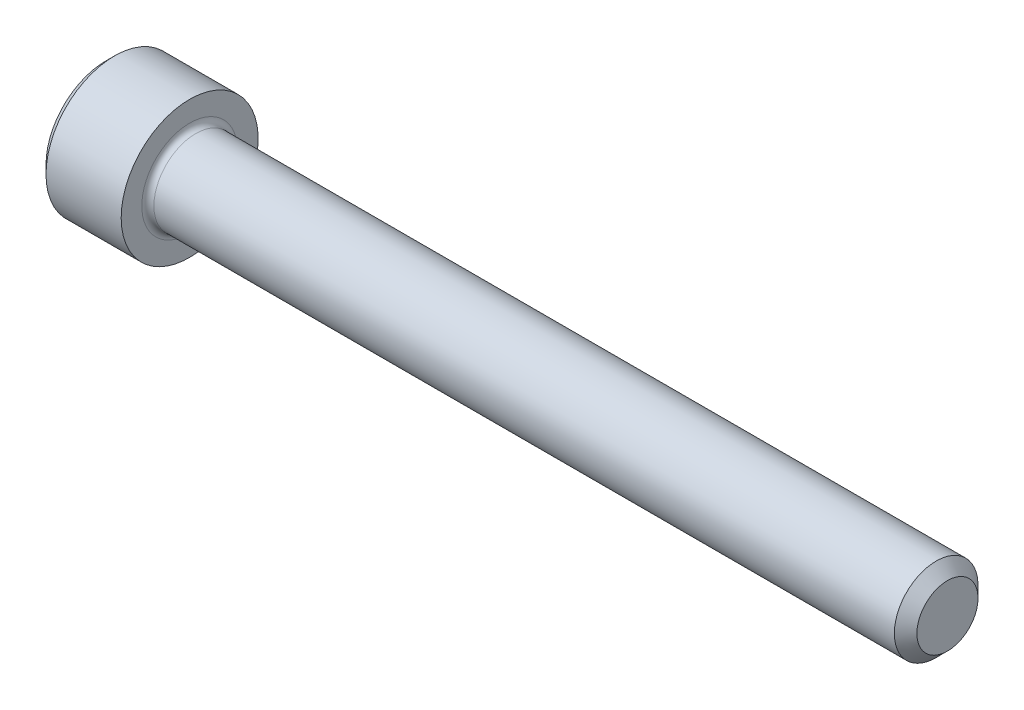
SolidWorks part; units mm, degrees
revolve "Base-Revolve" add sketch "BodySke" angle 360 about L6
sketch "BodySke" plane through (0, 0, 0) normal (0, 0, 1) x (1, 0, 0)
  line L0 (0, 0) -> (0, 2.5146)
  line L1 (0.3556, 2.8702) -> (3.5052, 2.8702)
  line L2 (3.5052, 2.8702) -> (3.5052, 1.7526)
  line L3 (3.5052, 1.7526) -> (34.7828, 1.7526)
  line L4 (35.2552, 1.2802) -> (35.2552, 0)
  line L5 (35.2552, 0) -> (0, 0)
  line L6 (-31.75, 0) -> (127, 0) construction
  line L7 (0, 2.5146) -> (0.3556, 2.8702)
  line L8 (35.2552, 1.2802) -> (34.7828, 1.7526)
  line L9 (0, -2.5146) -> (0.3556, -2.8702) construction
  line L10 (35.2552, -1.2802) -> (34.7828, -1.7526) construction
  line L11 (4.2977, 9.525) -> (4.2977, 3.175) construction
  line L12 (16.2052, 9.525) -> (16.2052, 3.175) construction
  line L13 (-2.8448, 9.525) -> (-2.8448, 3.175) construction
  dimension "Diameter" = 3.5052
  dimension "Head_ht" = 3.5052
  dimension "Length" = 31.75
  dimension "Body_ch_ang" = 45
  dimension "Head_dia" = 5.7404
  dimension "Head_ch_ang" = 45
  dimension "Head_side_ht" = 3.1496
  dimension "Minor_dia" = 2.5603
  dimension "Advance" = 0.7925
  dimension "Thread_nom" = 19.05
  dimension "Thread_length" = 38.1
cosmetic thread "ThreadCosmetic" parameters "Thread_length"=19.05, "Thread_minor"=2.5603
other "Defeature"
material "Alloy Steel"
ref_plane "Plane1" through (0, 0, 0) normal (0, 0, 1) x (1, 0, 0)
ref_plane "Plane2" through (0, 0, 0) normal (0, 1, 0) x (1, 0, 0)
ref_plane "Plane3" through (0, 0, 0) normal (1, 0, 0) x (0, 0, -1)
fillet "Fillet1" radius 0.254 1 edges at (3.5052, 0, 1.7526)
sketch "Sketch2" plane through (0, 0, 0) normal (0, 0, 1) x (1, 0, 0)
  line L0 (0, 1.3843) -> (1.6256, 1.3843)
  line L1 (1.6256, 1.3843) -> (2.4248, 0)
  line L2 (-31.75, 0) -> (127, 0) construction
  line L3 (2.4248, 0) -> (0, 0)
  line L4 (0, 0) -> (0, 1.3843)
  line L5 (0, 2.5146) -> (0, -2.5146) construction
  line L6 (0, 0) -> (47.625, 0) construction
  line L7 (3.5052, -2.8702) -> (3.5052, 2.8702) construction
  dimension "D1" = 1.3843
  dimension "D2" = 60
revolve "Hex-PreBroach" cut sketch "Sketch2" angle 360 about L6
sketch "Sketch3" plane through (0, 0, 0) normal (-1, 0, 0) x (0, 0.5, 0.866)
  line L0 (0.7992, 1.3843) -> (-0.7992, 1.3843)
  line L1 (-0.7992, 1.3843) -> (-1.5985, 0)
  line L2 (0.7992, 1.3843) -> (1.5985, 0)
  line L3 (0.7992, -1.3843) -> (1.5985, 0)
  line L4 (0.7992, -1.3843) -> (-0.7992, -1.3843)
  line L5 (-0.7992, -1.3843) -> (-1.5985, 0)
  dimension "D1" = 1.3843
  dimension "D2" = 1.3843
  dimension "Hex_size" = 2.7686
extrude "Hex" cut sketch "Sketch3" against normal blind 1.6256
sketch "Sketch4" plane through (0, 0, 0) normal (-1, 0, 0) x (0, 0, 1)
  line L0 (0, 0) -> (1.7399, 0)
  line L1 (0, 0) -> (6.1484, 3.5498) construction
  line L2 (0, 0) -> (0.8699, 1.5068)
  line L3 (1.4457, 0.3947) -> (1.6607, 0.5189)
  line L4 (1.0647, 1.0546) -> (1.2797, 1.1788)
  arc A0 (1.4457, 0.3947) -> (1.0647, 1.0546) centre (0, 0) ccw
  arc A1 (1.7399, 0) -> (1.6607, 0.5189) centre (0, 0) ccw
  arc A2 (0.8699, 1.5068) -> (1.2797, 1.1788) centre (0, 0) cw
  dimension "D1" = 30
  dimension "D2" = 60
  dimension "Spline_p_dim" = 0.762
  dimension "D3" = 0.381
extrude "Spline" [suppressed] cut sketch "Sketch4" against normal blind 1.6256
pattern_circular "CirPattern1" [suppressed] count 6 every 60 about axis through (-31.75, 0, 0) along (1, 0, 0)
sketch "Sketch5" plane through (0, 0, 0) normal (0, 0, 1) x (1, 0, 0)
  line L0 (-31.75, 0) -> (127, 0) construction
  line L2 (0, 2.5146) -> (0, -2.5146) construction
  circle A0 centre (1.27, 0) radius 0.4445
  dimension "Drilled_hole_dia" = 0.889
  dimension "Drilled_hole_loc" = 1.27
extrude "Hole" [suppressed] cut sketch "Sketch5" against normal through all and the other way through all
pattern_circular "Drilled-4" [suppressed] count 2 every 60 about axis through (-31.75, 0, 0) along (1, 0, 0)
pattern_circular "Drilled-6" [suppressed] count 3 every 60 about axis through (-31.75, 0, 0) along (1, 0, 0)
sketch "ThdSchSke" plane through (0, 0, 0) normal (0, 0, 1) x (1, 0, 0)
  line L0 (16.2052, -1.2802) -> (15.8744, -1.7526)
  line L1 (16.2052, -1.2802) -> (16.536, -1.7526)
  line L2 (16.536, -1.7526) -> (16.536, -2.1908)
  line L3 (-3.175, 0) -> (5.1513, 0) construction
  line L5 (16.536, -2.1908) -> (15.8744, -2.1908)
  line L6 (15.8744, -2.1908) -> (15.8744, -1.7526)
  line L7 (0, 2.5146) -> (0, -2.5146) construction
  dimension "Thread_minor" = 2.5603
  dimension "Diameter" = 3.5052
  dimension "Start" = 16.2052
revolve "ThreadSchematic" [suppressed] cut sketch "ThdSchSke" angle 360 about L3
pattern_linear "ThdSchPat" [suppressed]
equation "\"D2@Sketch3\" = \"Hex_size@Sketch3\" / 2"
equation "\"D1@Sketch3\" = \"Hex_size@Sketch3\" / 2"
equation "\"D1@Sketch2\" = \"Hex_size@Sketch3\" / 2"
equation "\"D3@Sketch4\" = \"Spline_p_dim@Sketch4\" / 2"
equation "\"Thread_minor@ThreadCosmetic\"  =  \"Minor_dia@BodySke\""
equation "\"D2@CirPattern1\" = 360 / \"Num_teeth@CirPattern1\""
equation "\"Wall_thickness@Sketch2\" = \"Head_ht@BodySke\" - \"Key_eng@Hex\""
equation "\"Thread_length@ThreadCosmetic\" = ((sgn( (\"Length@BodySke\" - \"Advance@BodySke\" ) - \"Thread_nom@BodySke\" )-1)*( (\"Length@BodySke\" - \"Advance@BodySke\" ) - \"Thread_nom@BodySke\" ))/-2+ \"Thread_nom@BodySke\""
equation "\"Thread_minor@ThdSchSke\" = \"Minor_dia@BodySke\""
equation "\"Diameter@ThdSchSke\" = \"Diameter@BodySke\""
equation "\"Overcut@ThdSchSke\" = \"Diameter@BodySke\" * 1.25"
equation "\"Start@ThdSchSke\" = \"Head_ht@BodySke\" + \"Length@BodySke\" - \"Thread_length@ThreadCosmetic\"  '---Non-countersunk---"
equation "\"Num_threads@ThdSchPat\" = int( \"Thread_length@ThreadCosmetic\" / \"Advance@BodySke\" + 0.999 )  + 1"
equation "\"Advance@ThdSchPat\" = \"Thread_length@ThreadCosmetic\" /  (\"Num_threads@ThdSchPat\" - 1) 'relax it"
equation "\"Num_threads@ThdSchPat\" = \"Num_threads@ThdSchPat\" - sgn( \"Num_threads@ThdSchPat\" - 1) '---chamfered tips only---"
